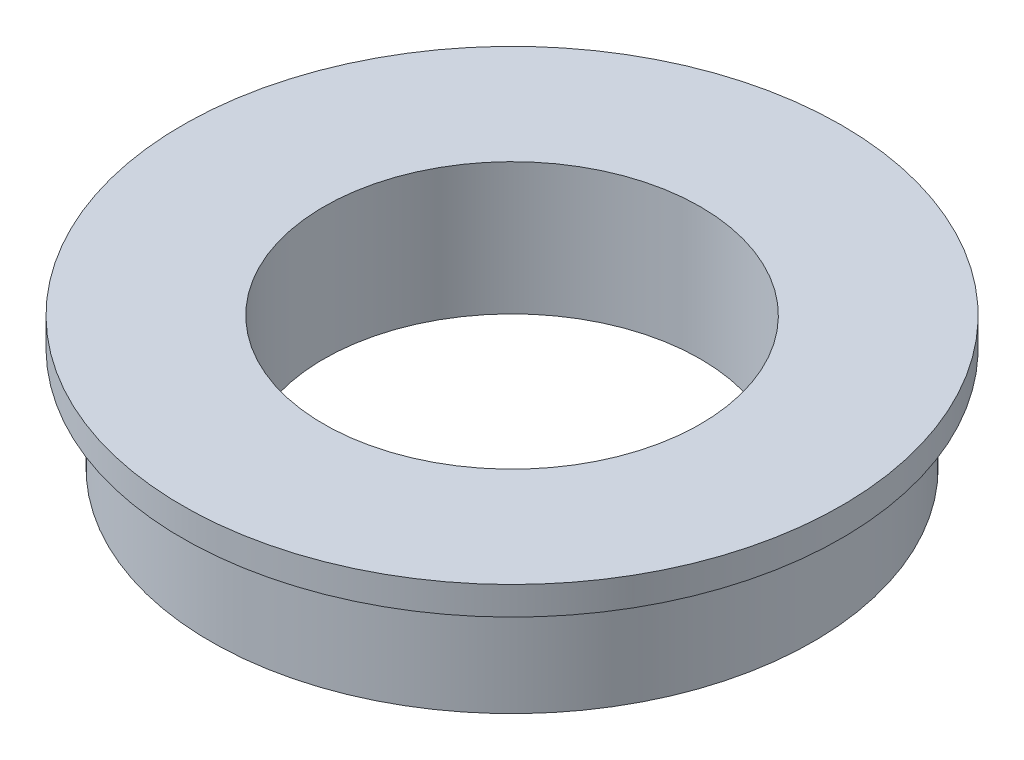
SolidWorks part; units mm, degrees
ref_plane "前视基准面" through (0, 0, 0) normal (0, 0, 1) x (1, 0, 0)
ref_plane "上视基准面" through (0, 0, 0) normal (0, 1, 0) x (1, 0, 0)
ref_plane "右视基准面" through (0, 0, 0) normal (1, 0, 0) x (0, 0, -1)
sketch "Sketch1" plane through (0, 0, 0) normal (0, 0, 1) x (1, 0, 0)
  line L0 (10, 0) -> (17.5, 0)
  line L1 (17.5, 0) -> (17.5, -1.5)
  line L2 (17.5, -1.5) -> (16, -1.5)
  line L3 (16, -1.5) -> (16, -7)
  line L4 (16, -7) -> (10, -7)
  line L5 (10, -7) -> (10, 0)
  line L6 (0, -7.3784) -> (0, 8.2134) construction
  dimension "D1" = 10
  dimension "D2" = 16
  dimension "D3" = 1.5
  dimension "D4" = 7
  dimension "D5" = 17.5
revolve "Revolve1" add sketch "Sketch1" angle 360 about L6
